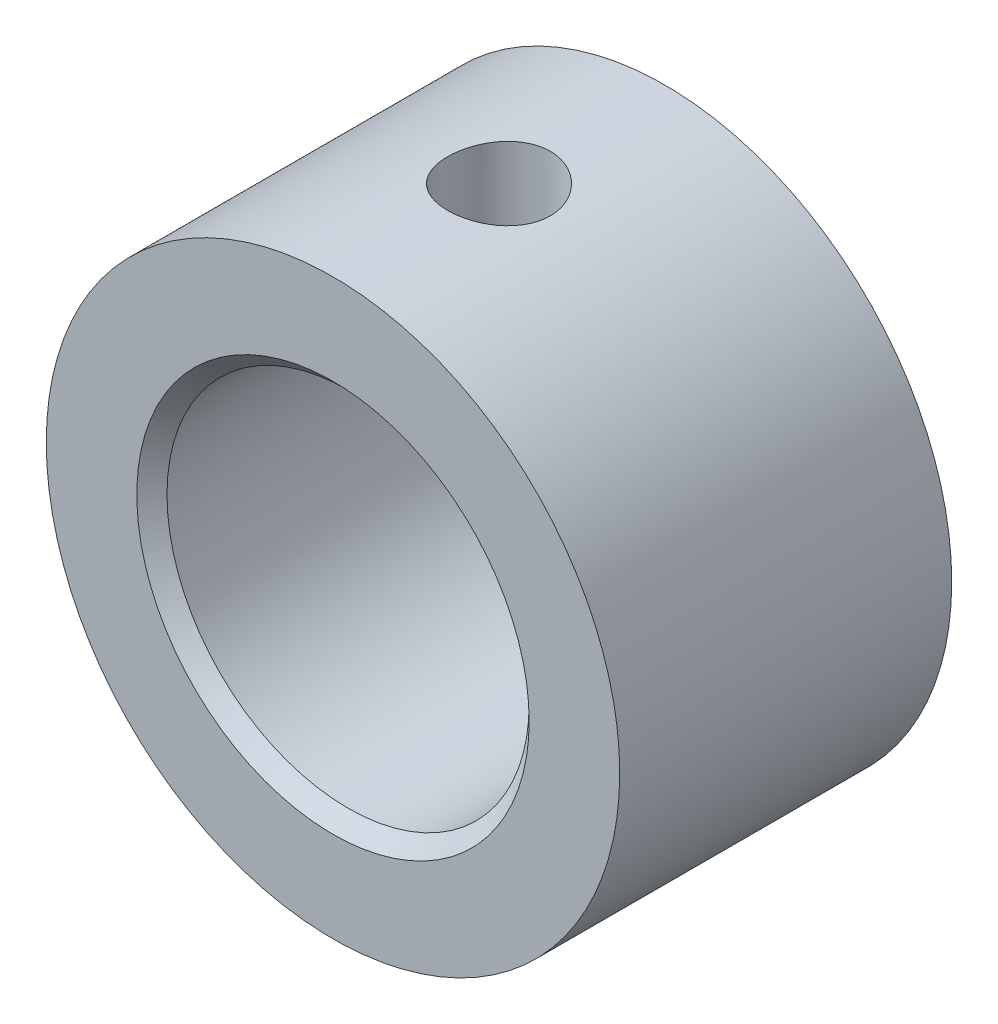
SolidWorks part; units mm, degrees
ref_plane "前视基准面" through (0, 0, 0) normal (0, 0, 1) x (1, 0, 0)
ref_plane "上视基准面" through (0, 0, 0) normal (0, 1, 0) x (1, 0, 0)
ref_plane "右视基准面" through (0, 0, 0) normal (1, 0, 0) x (0, 0, -1)
sketch "草图1" plane through (0, 0, 0) normal (0, 0, 1) x (1, 0, 0)
  circle A0 centre (0, 0) radius 19
  circle A1 centre (0, 0) radius 12
  dimension "D1" = 38
  dimension "D2" = 24
extrude "凸台-拉伸1" add sketch "草图1" along normal mid plane 22
chamfer "倒角1" distance 1 angle 45 2 edges at (12, 0, -11) (12, 0, 11)
sketch "草图2" plane through (0, 0, 0) normal (0, 1, 0) x (1, 0, 0)
  point P0 (0, 0)
hole_wizard "M8 螺纹孔1" positions "草图2" profile "草图3" tap size "M8" standard "GB"
sketch "草图3" plane through (0, 0, 0) normal (1, 0, 0) x (0, 0, -1)
  line L0 (0, 0) -> (0, 19)
  line L1 (0, 19) -> (3.4, 19)
  line L2 (3.4, 19) -> (3.4, 0)
  line L5 (3.4, 0) -> (0, 0)
  line L11 (0, -6.35) -> (0, 107.95) construction
  dimension "通孔螺纹孔钻头直径" = 6.8
  dimension "通孔螺纹孔钻头深度" = 19
cosmetic thread "孔螺纹线1" parameters "D2"=8
